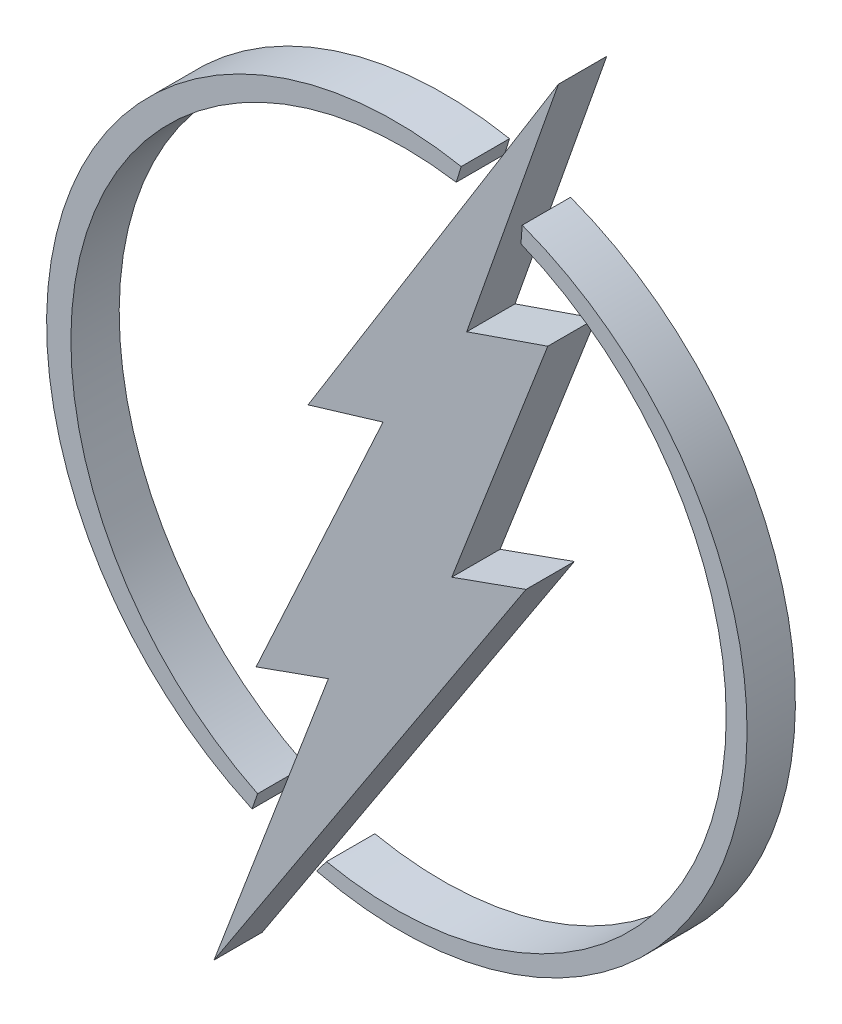
SolidWorks part; units mm, degrees
material "ABS"
ref_plane "Plan de face" through (0, 0, 0) normal (0, 0, 1) x (1, 0, 0)
ref_plane "Plan de dessus" through (0, 0, 0) normal (0, 1, 0) x (1, 0, 0)
ref_plane "Plan de droite" through (0, 0, 0) normal (1, 0, 0) x (0, 0, -1)
sketch "Esquisse1" plane through (0, 0, 0) normal (0, 0, 1) x (1, 0, 0)
  line L1 (0, 0) -> (10, 0)
  line L2 (0, 0) -> (0, 10)
  line L3 (0, 10) -> (10, 10)
  line L4 (10, 0) -> (10, 10)
  dimension "D1" = 10
extrude "Boss.-Extru.1" add sketch "Esquisse1" along normal blind 1
sketch "Esquisse2" plane through (0, 0, 1) normal (0, 0, 1) x (1, 0, 0)
  line L0 (37.5, 112.5) -> (187.5, 112.5) construction
  line L11 (37.5, 112.5) -> (187.5, 112.5) construction
  line L12 (6.3349, 8.8828) -> (4.2622, 5.5475)
  line L13 (4.2622, 5.5475) -> (4.8828, 5.7341)
  line L14 (4.8828, 5.7341) -> (3.8322, 3.4541)
  line L15 (3.8322, 3.4541) -> (4.4303, 3.6682)
  line L16 (4.4303, 3.6682) -> (3.4835, 1.1774)
  line L17 (3.4835, 1.1774) -> (6.0667, 5.1268)
  line L18 (6.0667, 5.1268) -> (5.4517, 4.9068)
  line L19 (5.4517, 4.9068) -> (6.2467, 6.9602)
  line L20 (6.2467, 6.9602) -> (5.5755, 6.7281)
  line L21 (5.5755, 6.7281) -> (6.3349, 8.8828)
  line L22 (5.5302, 7.89) -> (5.4885, 7.7563)
  line L23 (6.0244, 7.5829) -> (6.0352, 7.7224)
  line L24 (4.4151, 2.3494) -> (4.3333, 2.2411)
  line L25 (3.7985, 2.4186) -> (3.8444, 2.5508)
  arc A0 (6.0352, 7.7224) -> (4.3333, 2.2411) centre (5.0217, 5.0322) cw
  arc A1 (4.4151, 2.3494) -> (6.0244, 7.5829) centre (4.974, 5.0418) ccw
  arc A2 (5.4885, 7.7563) -> (3.8444, 2.5508) centre (5.0591, 5.0295) ccw
  arc A3 (3.7985, 2.4186) -> (5.5302, 7.89) centre (4.9871, 5.0521) cw
extrude "Boss.-Extru.2" add sketch "Esquisse2" along normal blind 0.4
sketch "Esquisse3" plane through (0, 0, 0) normal (0, 0, -1) x (-1, 0, 0)
  line L1 (-10.7647, 10.9757) -> (1.5157, 10.9757)
  line L2 (-10.7647, 10.9757) -> (-10.7647, -0.7082)
  line L3 (-10.7647, -0.7082) -> (1.5157, -0.7082)
  line L4 (1.5157, 10.9757) -> (1.5157, -0.7082)
extrude "Enlèv. mat.-Extru.1" cut sketch "Esquisse3" against normal blind 1
